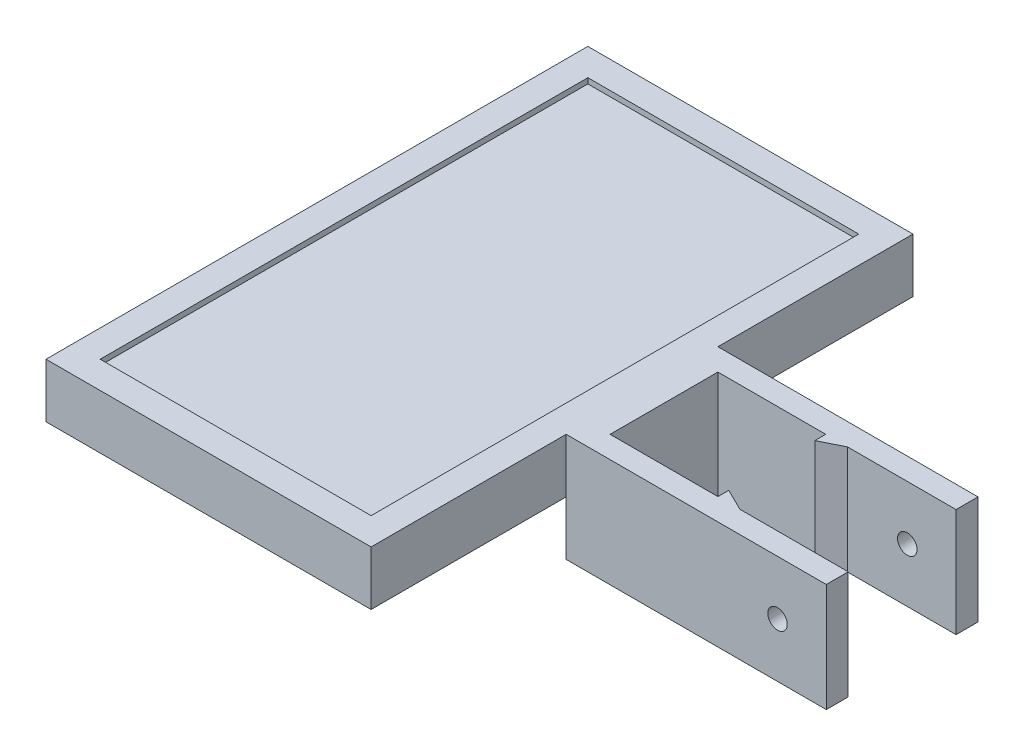
SolidWorks part; units mm, degrees
ref_plane "前视基准面" through (0, 0, 0) normal (0, 0, 1) x (1, 0, 0)
ref_plane "上视基准面" through (0, 0, 0) normal (0, 1, 0) x (1, 0, 0)
ref_plane "右视基准面" through (0, 0, 0) normal (1, 0, 0) x (0, 0, -1)
sketch "草图1" plane through (0, 0, 0) normal (0, 1, 0) x (1, 0, 0)
  line L1 (-9.95, -9.95) -> (9.95, -9.95)
  line L2 (-9.95, -9.95) -> (-9.95, 9.95)
  line L3 (-9.95, 9.95) -> (9.95, 9.95)
  line L4 (9.95, -9.95) -> (9.95, 9.95)
  line L5 (-9.95, -9.95) -> (9.95, 9.95) construction
  line L6 (-9.95, 9.95) -> (9.95, -9.95) construction
  line L7 (-14, -14) -> (14, -14)
  line L8 (-14, -14) -> (-14, 14)
  line L9 (-14, 14) -> (14, 14)
  line L10 (14, -14) -> (14, 14)
  line L11 (-14, -14) -> (14, 14) construction
  line L12 (-14, 14) -> (14, -14) construction
  point P0 (0, 0)
  point P5 (0, 0)
  dimension "D1" = 19.9
  dimension "D2" = 19.9
  dimension "D3" = 28
  dimension "D4" = 28
extrude "凸台-拉伸1" add sketch "草图1" along normal blind 20
sketch "草图2" plane through (0, 20, 0) normal (0, 1, 0) x (1, 0, 0)
  line L0 (14, 9.95) -> (9.95, 7.95)
  line L1 (14, -14) -> (14, 14) construction
  line L2 (9.95, -9.95) -> (9.95, 9.95) construction
  line L3 (9.95, 7.95) -> (9.95, -7.95)
  line L4 (9.95, -7.95) -> (14, -9.95)
  line L5 (14, -9.95) -> (14, 9.95)
  line L6 (0, 0) -> (3.4713, 0) construction
  line L7 (9.95, 9.95) -> (-9.95, 9.95) construction
  dimension "D1" = 2
extrude "切除-拉伸1" cut sketch "草图2" against normal blind 20
sketch "草图3" plane through (0, 20, 0) normal (0, 1, 0) x (1, 0, 0)
  line L0 (0, 0) -> (9.2107, 0) construction
  line L1 (14, 9.95) -> (34, 9.95)
  line L2 (14, 9.95) -> (14, 14)
  line L3 (14, 14) -> (34, 14)
  line L4 (34, 9.95) -> (34, 14)
  line L5 (14, 14) -> (-14, 14) construction
  line L6 (14, -14) -> (34, -14)
  line L7 (34, -9.95) -> (34, -14)
  line L8 (14, -9.95) -> (34, -9.95)
  line L9 (14, -9.95) -> (14, -14)
  dimension "D1" = 20
extrude "凸台-拉伸2" add sketch "草图3" against normal blind 20
sketch "草图4" plane through (0, 0, -9.95) normal (0, 0, 1) x (1, 0, 0)
  line L0 (-14, 20) -> (34, 20) construction
  line L2 (34, 0) -> (34, 20) construction
  circle A0 centre (25, 10) radius 1.8
  dimension "D1" = 3.6
  dimension "D2" = 10
  dimension "D3" = 9
extrude "切除-拉伸2" cut sketch "草图4" against normal up to next and the other way up to surface other way up to face at (10, 10, 14)
sketch "草图5" plane through (0, 20, 0) normal (0, 1, 0) x (1, 0, 0)
  line L0 (-14, 14) -> (-14, -14) construction
  line L1 (-14, 50) -> (-74, 50)
  line L2 (-14, 50) -> (-14, -50)
  line L3 (-14, -50) -> (-74, -50)
  line L4 (-74, 50) -> (-74, -50)
  line L5 (0, 0) -> (-6.3447, 0) construction
  dimension "D1" = 100
  dimension "D2" = 60
extrude "凸台-拉伸3" add sketch "草图5" against normal blind 10
sketch "草图6" plane through (-14, 0, 0) normal (-1, 0, 0) x (0, 0, 1)
  line L0 (14, 10) -> (-14, 10) construction
  line L1 (-5, 10) -> (5, 10)
  line L2 (-5, 10) -> (-5, 0)
  line L3 (-5, 0) -> (5, 0)
  line L4 (5, 10) -> (5, 0)
  line L5 (-14, 0) -> (14, 0) construction
  line L6 (0, -0.2345) -> (0, -4.0232) construction
  dimension "D1" = 10
extrude "凸台-拉伸4" add sketch "草图6" along normal up to surface (60 mm away) up to face at (-74, 15, 0)
sketch "草图7" plane through (0, 0, 5) normal (0, 0, 1) x (1, 0, 0)
  line L0 (-74, 10) -> (-74, 0)
  line L1 (-74, 10) -> (-14, 10) construction
  line L2 (-74, 10) -> (-14, 10) construction
  line L3 (-74, 0) -> (-14, 0) construction
  line L4 (-74, 0) -> (-14, 0)
  line L5 (-14, 0) -> (-74, 10)
extrude "切除-拉伸3" cut sketch "草图7" against normal up to next
sketch "草图8" plane through (0, 20, 0) normal (0, 1, 0) x (1, 0, 0)
  line L0 (-14, 50) -> (-74, 50) construction
  line L1 (-69, 45) -> (-19, 45)
  line L2 (-69, 45) -> (-69, -45)
  line L3 (-69, -45) -> (-19, -45)
  line L4 (-19, 45) -> (-19, -45)
  line L5 (-74, 50) -> (-74, -50) construction
  line L6 (-14, 14) -> (-14, 50) construction
  line L7 (-74, -50) -> (-14, -50) construction
  dimension "D1" = 5
  dimension "D2" = 5
  dimension "D3" = 5
  dimension "D4" = 5
extrude "切除-拉伸4" cut sketch "草图8" against normal blind 1
